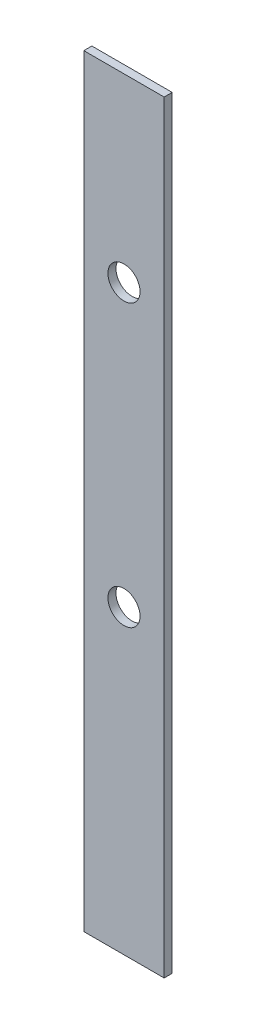
SolidWorks part; units mm, degrees
ref_plane "Front Plane" through (0, 0, 0) normal (0, 0, 1) x (1, 0, 0)
ref_plane "Top Plane" through (0, 0, 0) normal (0, 1, 0) x (1, 0, 0)
ref_plane "Right Plane" through (0, 0, 0) normal (1, 0, 0) x (0, 0, -1)
sketch "Sketch1" plane through (0, 0, 0) normal (0, 0, 1) x (1, 0, 0)
  line L1 (-20, 190) -> (20, 190)
  line L2 (-20, 190) -> (-20, -190)
  line L3 (-20, -190) -> (20, -190)
  line L4 (20, 190) -> (20, -190)
  line L9 (-20, 270) -> (20, 270)
  point P0 (0, 0)
  dimension "D6" = 80
extrude "Boss-Extrude1" add sketch "Sketch1" along normal blind 4 contours L1 L4 L3 L2
ref_plane "Plane1" through (0, 0, 0) normal (0, 0, -1) x (-1, 0, 0)
sketch "Sketch2" plane through (0, 0, 0) normal (0, 0, -1) x (-1, 0, 0)
  line L0 (20, 190) -> (-20, 190) construction
  line L1 (20, -190) -> (-20, -190) construction
  line L4 (20, 100) -> (-20, 100) construction
  line L5 (20, -40) -> (-20, -40) construction
  line L6 (20, -330) -> (-20, -330)
  circle A0 centre (0, 100) radius 8
  circle A1 centre (0, -40) radius 8
  dimension "D1" = 16
  dimension "D2" = 16
  dimension "D3" = 90
  dimension "D4" = 150
extrude "Cut-Extrude1" cut sketch "Sketch2" against normal blind 4 contours A0 | A1
